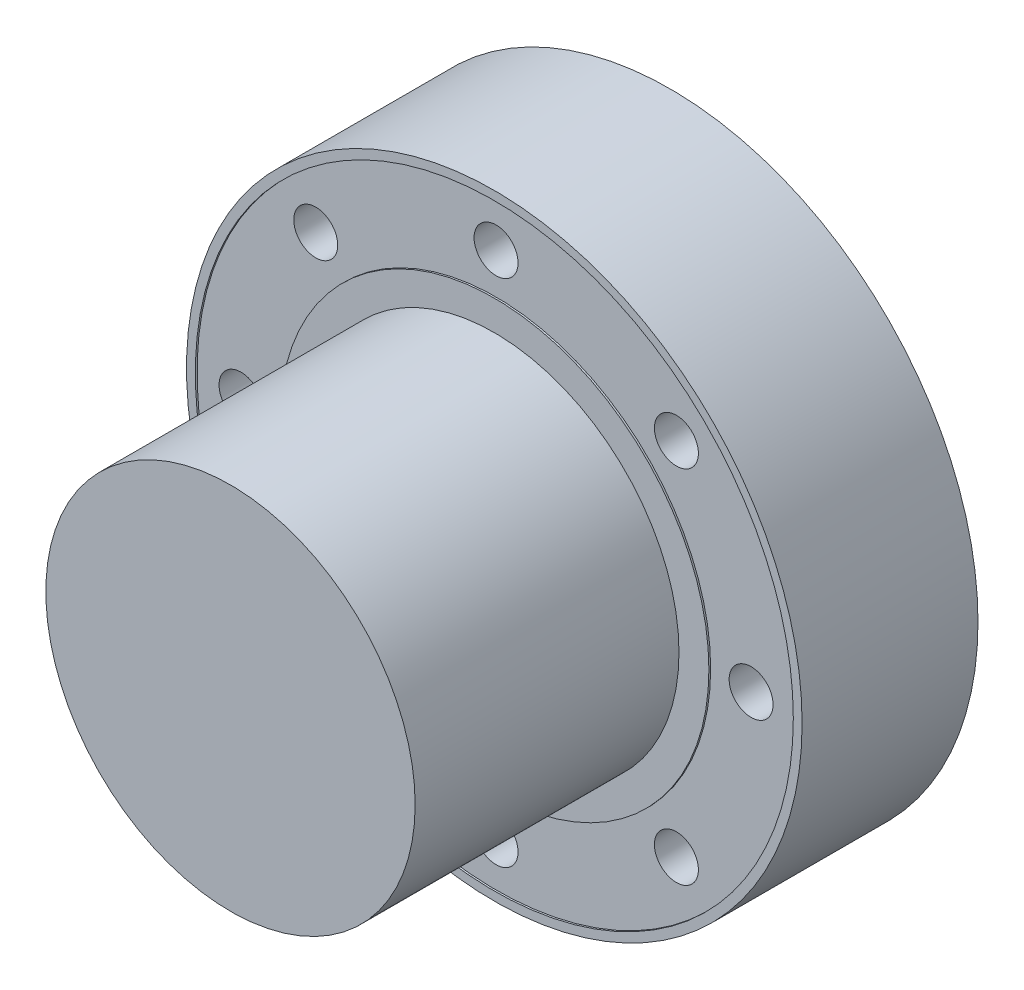
SolidWorks part; units mm, degrees
ref_plane "前视基准面" through (0, 0, 0) normal (0, 0, 1) x (1, 0, 0)
ref_plane "上视基准面" through (0, 0, 0) normal (0, 1, 0) x (1, 0, 0)
ref_plane "右视基准面" through (0, 0, 0) normal (1, 0, 0) x (0, 0, -1)
sketch "草图1" plane through (0, 0, 0) normal (0, 0, 1) x (1, 0, 0)
  circle A0 centre (0, 0) radius 350
  dimension "D1" = 700
extrude "凸台-拉伸1" add sketch "草图1" along normal blind 200
sketch "草图2" plane through (0, 0, 200) normal (0, 0, 1) x (1, 0, 0)
  circle A0 centre (0, 0) radius 210
  circle A1 centre (0, 0) radius 350 construction
  dimension "D1" = 140
extrude "凸台-拉伸2" add sketch "草图2" along normal blind 300
sketch "草图3" plane through (0, 0, 200) normal (0, 0, 1) x (1, 0, 0)
  circle A0 centre (0, 0) radius 340
  circle A1 centre (0, 0) radius 350 construction
  circle A2 centre (0, 0) radius 244
  dimension "D1" = 10
  dimension "D2" = 96
extrude "切除-拉伸1" cut sketch "草图3" against normal blind 2
sketch "草图4" plane through (0, 0, 0) normal (0, 0, -1) x (-1, 0, 0)
  line L0 (0, 0) -> (0, 290) construction
  circle A0 centre (0, 290) radius 25
  dimension "D1" = 50
  dimension "D2" = 290
extrude "切除-拉伸2" cut sketch "草图4" against normal through all
pattern_circular "阵列(圆周)1" count 8 over 360 about axis through (0, 0, 0) along (0, 0, 1) of "切除-拉伸2"
